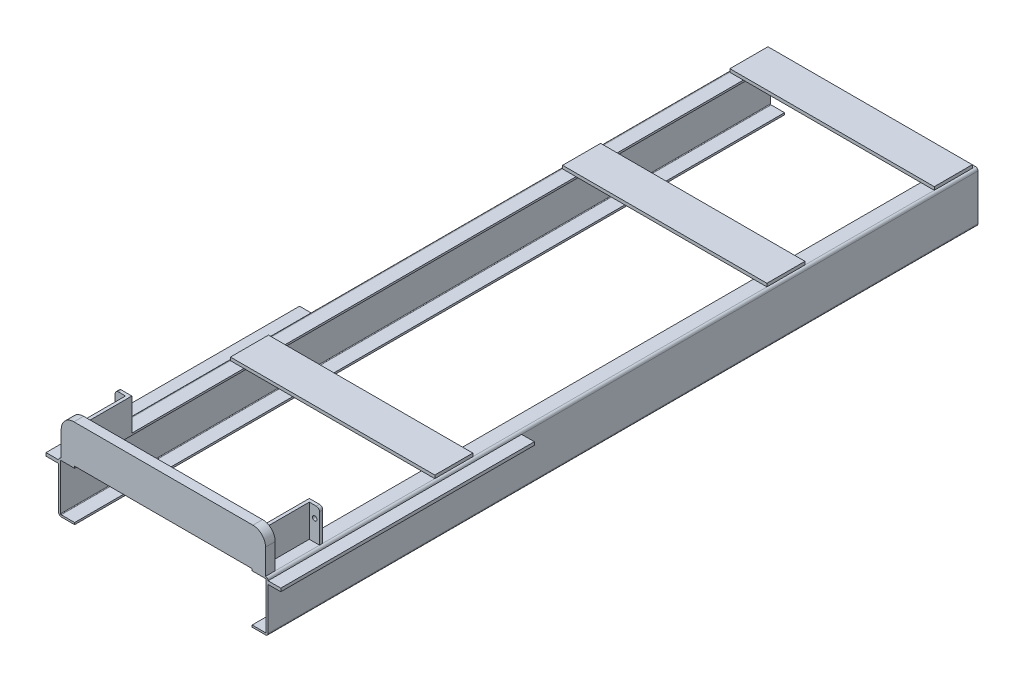
SolidWorks part; units mm, degrees
ref_plane "Front Plane" through (0, 0, 0) normal (0, 0, 1) x (1, 0, 0)
ref_plane "Top Plane" through (0, 0, 0) normal (0, 1, 0) x (1, 0, 0)
ref_plane "Right Plane" through (0, 0, 0) normal (1, 0, 0) x (0, 0, -1)
sketch "Sketch1" plane through (0, 0, 0) normal (0, 0, 1) x (1, 0, 0)
  line L0 (0, 0) -> (413, 0) construction
  line L1 (350, 100) -> (403, 100)
  line L2 (413, 90) -> (413, -90)
  line L3 (403, -100) -> (350, -100)
  arc A0 (403, 100) -> (413, 90) centre (403, 90) cw
  arc A1 (413, -90) -> (403, -100) centre (403, -90) cw
  point P9 (413, 100)
  point P12 (413, -100)
  dimension "D6" = 10
  dimension "D7" = 10
  dimension "D1" = 413
  dimension "D2" = 200
  dimension "D3" = 63
  dimension "D4" = 100
  dimension "D5" = 63
extrude "Extrude-Thin1" add sketch "Sketch1" along normal mid plane 2800 thin contours L1 A0 L2 A1 L3
sketch "Sketch3" plane through (0, 0, 1400) normal (0, 0, 1) x (1, 0, 0)
  line L1 (413, 90) -> (463, 90)
  line L2 (413, 90) -> (413, 77.5)
  line L3 (413, 77.5) -> (463, 77.5)
  line L4 (463, 90) -> (463, 77.5)
  dimension "D1" = 50
  dimension "D2" = 12.5
extrude "Boss-Extrude1" add sketch "Sketch3" against normal blind 1000 contours L1 L4 L3 L2
mirror "Mirror2" about plane through (0, 0, 0) normal (1, 0, 0) of bodies 102
sketch "Sketch4" plane through (0, 0, 1400) normal (0, 0, 1) x (1, 0, 0)
  line L1 (-403, 100) -> (403, 100)
  line L2 (-403, 100) -> (-403, 200)
  line L3 (-353, 250) -> (353, 250)
  line L4 (403, 100) -> (403, 200)
  arc A0 (-403, 200) -> (-353, 250) centre (-353, 200) cw
  arc A1 (353, 250) -> (403, 200) centre (353, 200) cw
  point P10 (403, 250)
  dimension "D2" = 50
  dimension "D1" = 150
extrude "Boss-Extrude2" add sketch "Sketch4" against normal blind 38
sketch "Sketch5" plane through (0, 100, 0) normal (0, 1, 0) x (1, 0, 0)
  line L0 (-403, -1362) -> (-403, 1400) construction
  line L1 (-403, 1387.5) -> (403, 1387.5)
  line L2 (-403, 1387.5) -> (-403, 1237.5)
  line L3 (-403, 1237.5) -> (403, 1237.5)
  line L4 (403, 1387.5) -> (403, 1237.5)
  line L5 (403, -1362) -> (403, 1400) construction
  line L6 (350, 1400) -> (403, 1400) construction
  point P10 (376.5, 1400)
  dimension "D1" = 12.5
  dimension "D2" = 150
extrude "Boss-Extrude3" add sketch "Sketch5" along normal blind 12.5
pattern_linear "LPattern1" count 2 spacing 660 along (0, 0, 1) of "Boss-Extrude3"
pattern_linear "LPattern2" count 2 spacing 1970 along (0, 0, 1) of "Boss-Extrude3"
sketch "Sketch6" plane through (0, 0, 1362) normal (0, 0, -1) x (-1, 0, 0)
  line L1 (-350, 100) -> (-362.5, 100)
  line L2 (-350, 100) -> (-350, 227)
  line L3 (-350, 227) -> (-362.5, 227)
  line L4 (-362.5, 100) -> (-362.5, 227)
  dimension "D1" = 127
  dimension "D2" = 12.5
extrude "Boss-Extrude4" add sketch "Sketch6" along normal blind 175
sketch "Sketch7" plane through (0, 0, 1187) normal (0, 0, -1) x (-1, 0, 0)
  line L1 (-350, 100) -> (-403, 100)
  line L2 (-350, 100) -> (-350, 227)
  line L3 (-350, 227) -> (-403, 227)
  line L4 (-403, 100) -> (-403, 227)
  circle A0 centre (-384, 182) radius 8.75
  dimension "D1" = 17.5
  dimension "D2" = 82
  dimension "D3" = 19
extrude "Boss-Extrude5" add sketch "Sketch7" along normal blind 12.5
fillet "Fillet1" radius 12.5 1 edges at (403, 227, 1180.75)
mirror "Mirror3" about plane through (0, 0, 0) normal (1, 0, 0) of "Fillet1", "Boss-Extrude5", "Boss-Extrude4"
